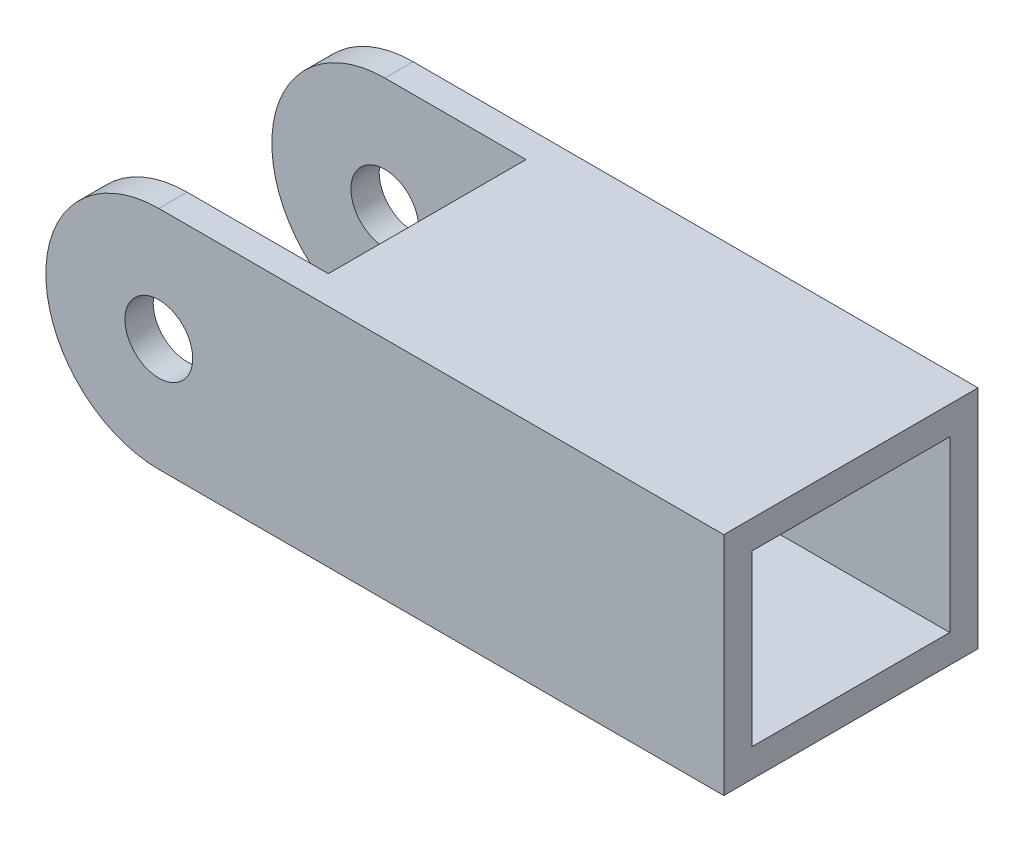
SolidWorks part; units mm, degrees
ref_plane "Płaszczyzna przednia" through (0, 0, 0) normal (0, 0, 1) x (1, 0, 0)
ref_plane "Płaszczyzna górna" through (0, 0, 0) normal (0, 1, 0) x (1, 0, 0)
ref_plane "Płaszczyzna prawa" through (0, 0, 0) normal (1, 0, 0) x (0, 0, -1)
sketch "Szkic1" plane through (0, 0, 0) normal (0, 0, 1) x (1, 0, 0)
  line L1 (-50, -20) -> (50, -20)
  line L3 (-50, 20) -> (50, 20)
  line L4 (50, -20) -> (50, 20)
  line L5 (-50, -20) -> (50, 20) construction
  line L6 (-50, 20) -> (50, -20) construction
  arc A0 (-50, -20) -> (-50, 20) centre (-50, 0) cw
  point P0 (0, 0)
  dimension "D1" = 40
  dimension "D2" = 100
extrude "Dodanie-wyciągnięcie1" add sketch "Szkic1" along normal blind 5 contours L3 L4 L1 A0
ref_plane "Płaszczyzna1" through (0, 0, 22.5) normal (0, 0, 1) x (1, 0, 0)
mirror "Lustro2" about plane through (0, 0, 22.5) normal (0, 0, 1) of bodies 101
ref_plane "Płaszczyzna2" through (0, 20, 0) normal (0, 1, 0) x (1, 0, 0)
sketch "Szkic2" plane through (0, 20, 0) normal (0, 1, 0) x (1, 0, 0)
  line L0 (-50, -5) -> (50, -5) construction
  line L1 (50, -40) -> (-25, -40)
  line L2 (50, -40) -> (50, -5)
  line L3 (50, -5) -> (-25, -5)
  line L4 (-25, -40) -> (-25, -5)
  dimension "D1" = 75
extrude "Dodanie-wyciągnięcie2" add sketch "Szkic2" against normal blind 5
mirror "Lustro5" about plane through (0, 0, 0) normal (0, 1, 0) of "Dodanie-wyciągnięcie2"
sketch "Szkic3" plane through (0, 0, 0) normal (0, 0, -1) x (-1, 0, 0)
  circle A0 centre (50, 0) radius 6
  arc A1 (50, -20) -> (50, 20) centre (50, 0) ccw construction
  dimension "D1" = 12
extrude "Wytnij-wyciągnięcie1" cut sketch "Szkic3" against normal through all
